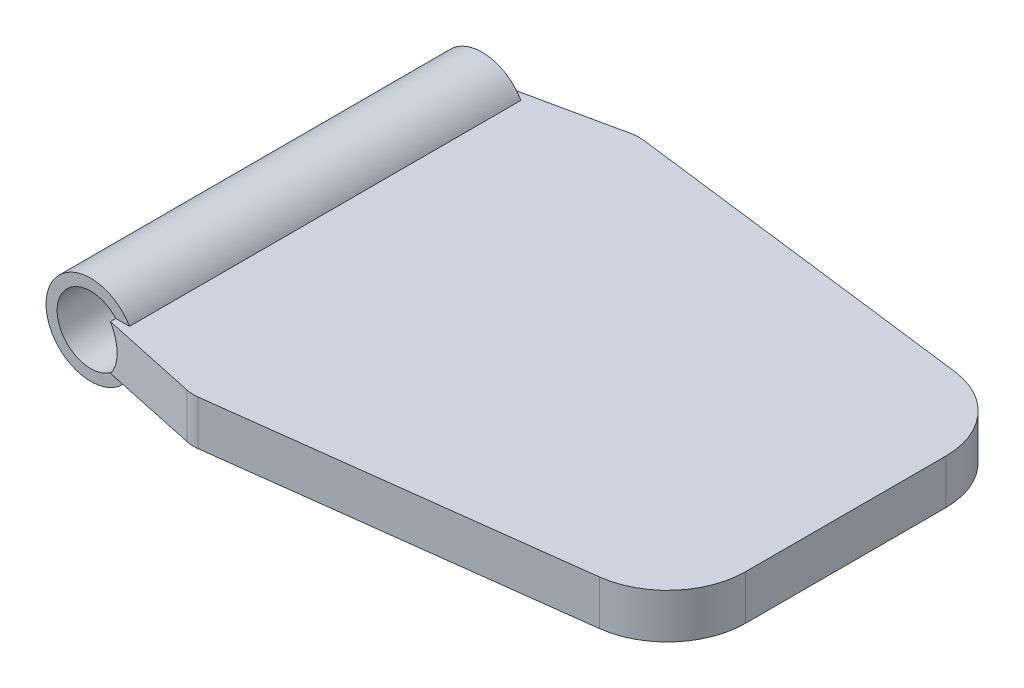
SolidWorks part; units mm, degrees
ref_plane "Front Plane" through (0, 0, 0) normal (0, 0, 1) x (1, 0, 0)
ref_plane "Top Plane" through (0, 0, 0) normal (0, 1, 0) x (1, 0, 0)
ref_plane "Right Plane" through (0, 0, 0) normal (1, 0, 0) x (0, 0, -1)
sketch "Sketch1" plane through (0, 0, 0) normal (0, 1, 0) x (1, 0, 0)
  line L0 (0, 0) -> (0, -88.9) construction
  line L1 (0, -88.9) -> (127, -88.9) construction
  line L2 (0, 0) -> (27.8998, 5.9958)
  line L3 (30.4519, 6.1064) -> (111.4391, -4.0814)
  line L4 (0, -44.45) -> (61.4721, -44.45) construction
  line L5 (30.4519, -95.0064) -> (111.4391, -84.8186)
  line L6 (0, -88.9) -> (27.8998, -94.8958)
  line L7 (127, -21.7224) -> (127, -67.1776)
  line L8 (0, 0) -> (0, -88.9)
  arc A0 (30.4519, -95.0064) -> (27.8998, -94.8958) centre (29.5008, -87.4459) cw
  arc A1 (30.4519, 6.1064) -> (27.8998, 5.9958) centre (29.5008, -1.4541) ccw
  arc A2 (111.4391, -84.8186) -> (127, -67.1776) centre (109.22, -67.1776) ccw
  arc A3 (127, -21.7224) -> (111.4391, -4.0814) centre (109.22, -21.7224) ccw
  point P12 (29.1664, -95.1681)
  point P15 (29.1664, 6.2681)
  point P18 (127, -82.8611)
  point P21 (127, -6.0389)
  dimension "D1" = 7.62
  dimension "D2" = 17.78
extrude "Boss-Extrude1" add sketch "Sketch1" along normal blind 10.16
ref_plane "Plane1" through (0, 0, -7.62) normal (0, 0, 1) x (1, 0, 0)
sketch "Sketch3" plane through (0, 0, -7.62) normal (0, 0, 1) x (1, 0, 0)
  line L0 (0, 10.16) -> (0, 0) construction
  circle A0 centre (0, 5.08) radius 7.62
  circle A1 centre (0, 5.08) radius 10.16
sketch "Sketch4" plane through (0, 0, 0) normal (0, 0, 1) x (1, 0, 0)
  circle A0 centre (0, 5.08) radius 10.16 construction
  circle A1 centre (0, 5.08) radius 10.16
extrude "Boss-Extrude2" add sketch "Sketch4" along normal blind 88.9
sketch "Sketch5" plane through (0, 0, 0) normal (0, 0, 1) x (1, 0, 0)
  circle A0 centre (0, 5.08) radius 7.62 construction
  circle A1 centre (0, 5.08) radius 7.62
extrude "Cut-Extrude1" cut sketch "Sketch5" against normal through all and the other way through all
